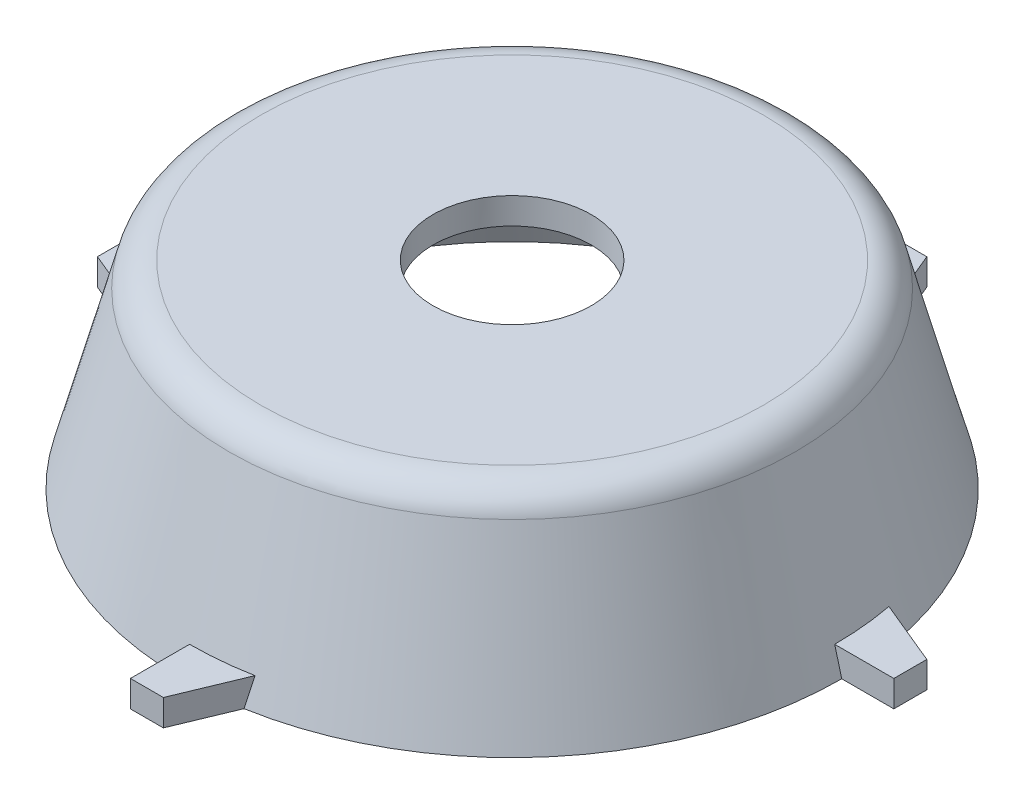
SolidWorks part; units mm, degrees
ref_plane "Alzado" through (0, 0, 0) normal (0, 0, 1) x (1, 0, 0)
ref_plane "Planta" through (0, 0, 0) normal (0, 1, 0) x (1, 0, 0)
ref_plane "Vista lateral" through (0, 0, 0) normal (1, 0, 0) x (0, 0, -1)
sketch "Croquis3" plane through (0, 0, 0) normal (1, 0, 0) x (0, 0, -1)
  line L0 (0, 0) -> (60574.949, 0) construction
  line L1 (0, 0) -> (0, 60574.949) construction
  line L3 (0, 0) -> (-50, 0)
  line L4 (0, 0) -> (0, 30)
  line L5 (0, 30) -> (-50, 30)
  line L6 (-50, 0) -> (-50, 30)
  dimension "D1" = 50
  dimension "D2" = 30
revolve "Revolución1" add sketch "Croquis3" angle 360 about L1
sketch "Croquis6" plane through (0, 0, 0) normal (0, 0, 1) x (1, 0, 0)
  line L0 (-50, 0) -> (-50, -50000) construction
  line L1 (-50, 0) -> (-50050, 0) construction
  line L2 (50, 30) -> (-50, 30) construction
  line L3 (0, 0) -> (-50, 0)
  line L4 (0, 0) -> (0, 30)
  line L5 (0, 30) -> (-50, 30)
  line L6 (-50, 0) -> (-50, 30)
  line L7 (-50, 0) -> (-41.9615, 30)
  line L8 (0, -970) -> (0, 49030) construction
  dimension "D1" = 105
revolve "Cortar-Revolución1" cut sketch "Croquis6" angle 360 about L8
shell "Vaciado1" thickness 4
ref_plane "Plano1" through (0, 30, 0) normal (0, 1, 0) x (1, 0, 0)
sketch "Croquis7" plane through (0, 30, 0) normal (0, 1, 0) x (1, 0, 0)
  circle A0 centre (0, 0) radius 12
  dimension "D1" = 24
extrude "Cortar-Extruir1" cut sketch "Croquis7" against normal up to next
fillet "Redondeo1" radius 5 1 edges at (41.9615, 30, 0)
ref_plane "Plano2" through (0, 0, 0) normal (0, -1, 0) x (-1, 0, 0)
sketch "Croquis8" plane through (0, 0, 0) normal (0, -1, 0) x (-1, 0, 0)
  line L0 (0, 0) -> (0, 50000) construction
  line L1 (0, 0) -> (50000, 0) construction
  line L2 (0, 57.8995) -> (5, 57.8995)
  line L3 (0, 45.8589) -> (10, 45.8589)
  line L4 (0, 45.8589) -> (0, 57.8995)
  line L5 (5, 57.8995) -> (10, 45.8589)
  circle A0 centre (0, 0) radius 45.8589 construction
  dimension "D1" = 10
  dimension "D2" = 5
  dimension "D3" = 13.0375
extrude "Saliente-Extruir1" add sketch "Croquis8" against normal blind 4
mirror "Simetría1" about plane through (0, 4, -45.8589) normal (1, 0, 0) of "Saliente-Extruir1"
pattern_circular "MatrizC10" count 4 over 360 about axis through (0, 0, 0) along (0, 1, 0) of "Saliente-Extruir1"
